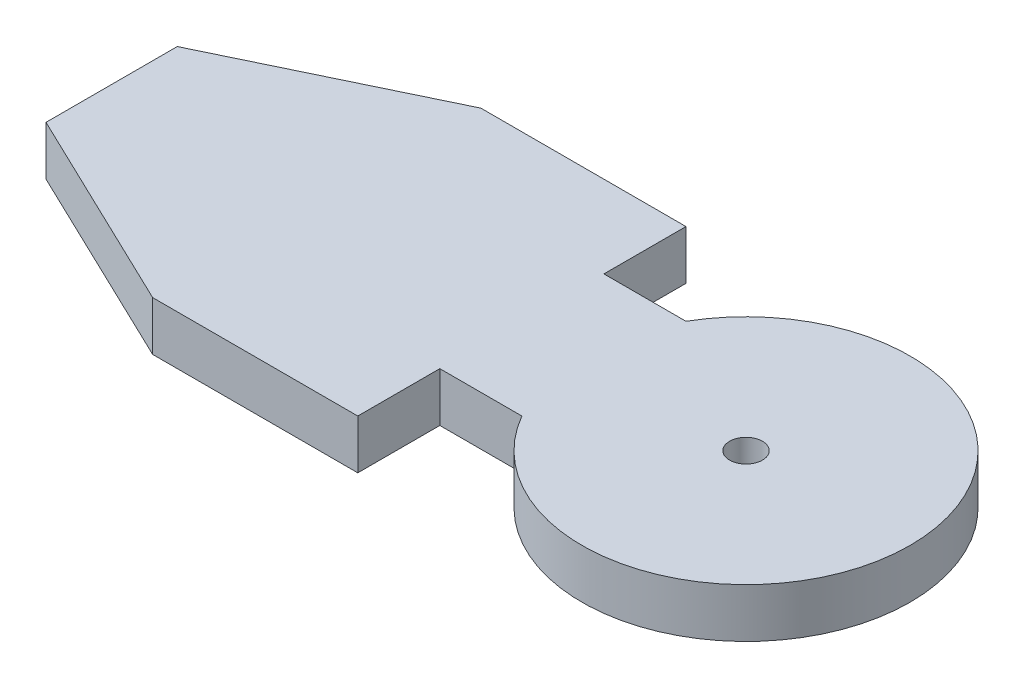
SolidWorks part; units mm, degrees
ref_plane "Front Plane" through (0, 0, 0) normal (0, 0, 1) x (1, 0, 0)
ref_plane "Top Plane" through (0, 0, 0) normal (0, 1, 0) x (1, 0, 0)
ref_plane "Right Plane" through (0, 0, 0) normal (1, 0, 0) x (0, 0, -1)
sketch "Sketch1" plane through (0, 0, 0) normal (0, 1, 0) x (1, 0, 0)
  line L0 (-12.5, 0) -> (-25, 6)
  line L1 (0, 0) -> (-12.5, 0)
  line L2 (0, 0) -> (0, 5)
  line L3 (0, 20) -> (-12.5, 20)
  line L4 (-25, 6) -> (-25, 14)
  line L5 (-12.5, 20) -> (-25, 14)
  line L7 (0, 15) -> (5, 15)
  line L8 (0, 5) -> (5, 5)
  line L9 (0, 15) -> (0, 20)
  arc A0 (5, 15) -> (5, 5) centre (13.6603, 10) cw
  point P10 (0, 10)
  dimension "D4" = 10
  dimension "D1" = 25
  dimension "20" = 20
  dimension "D2" = 10
  dimension "D3" = 5
extrude "Boss-Extrude1" add sketch "Sketch1" along normal blind 3
sketch "Sketch2" plane through (0, 3, 0) normal (0, 1, 0) x (1, 0, 0)
  circle A0 centre (13.6603, 10) radius 1
  dimension "D1" = 2
extrude "Cut-Extrude1" cut sketch "Sketch2" against normal blind 13
